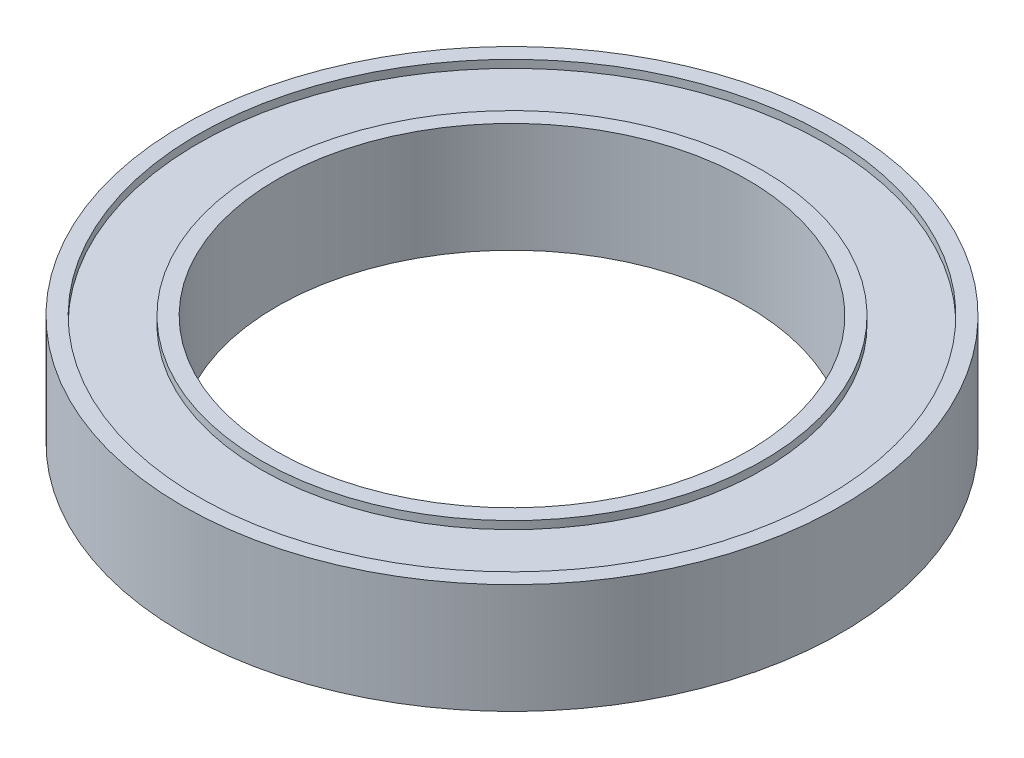
SolidWorks part; units mm, degrees
ref_plane "Front Plane" through (0, 0, 0) normal (0, 0, 1) x (1, 0, 0)
ref_plane "Top Plane" through (0, 0, 0) normal (0, 1, 0) x (1, 0, 0)
ref_plane "Right Plane" through (0, 0, 0) normal (1, 0, 0) x (0, 0, -1)
sketch "Sketch1" plane through (0, 0, 0) normal (0, 1, 0) x (1, 0, 0)
  circle A0 centre (0, 0) radius 15
  circle A1 centre (0, 0) radius 21
  dimension "D1" = 42
  dimension "D2" = 30
extrude "Boss-Extrude1" add sketch "Sketch1" along normal mid plane 7
sketch "Sketch2" plane through (0, 3.5, 0) normal (0, 1, 0) x (1, 0, 0)
  circle A2 centre (0, 0) radius 16
  circle A3 centre (0, 0) radius 16
  circle A6 centre (0, 0) radius 20
  circle A7 centre (0, 0) radius 20
  dimension "D1" = 1
  dimension "D2" = 1
extrude "Cut-Extrude1" cut sketch "Sketch2" against normal blind 0.5 and the other way through all
mirror "Mirror1" about plane through (0, 0, 0) normal (0, 1, 0) of "Cut-Extrude1"
